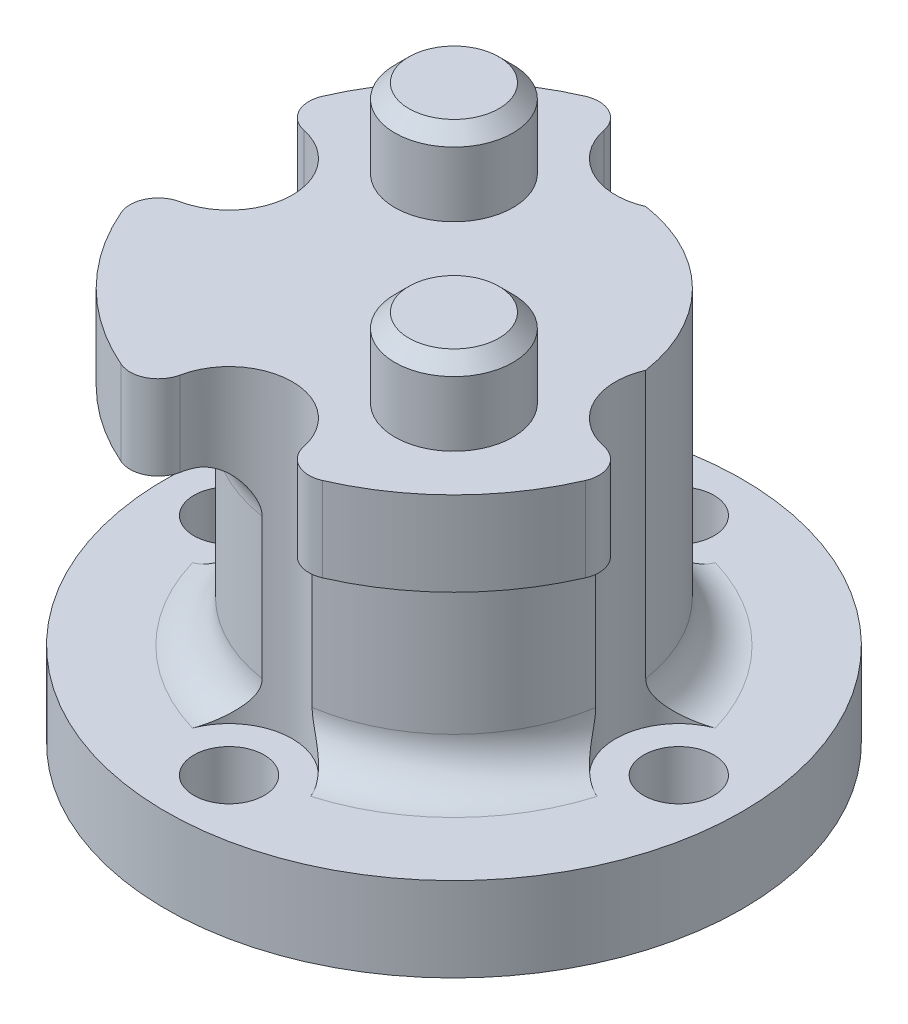
SolidWorks part; units mm, degrees
ref_plane "前视基准面" through (0, 0, 0) normal (0, 0, 1) x (1, 0, 0)
ref_plane "上视基准面" through (0, 0, 0) normal (0, 1, 0) x (1, 0, 0)
ref_plane "右视基准面" through (0, 0, 0) normal (1, 0, 0) x (0, 0, -1)
sketch "Sketch2" plane through (0, 0, 0) normal (0, 0, 1) x (1, 0, 0)
  line L0 (0, 0) -> (10.25, 0)
  line L1 (10.25, 0) -> (10.25, 3)
  line L2 (10.25, 3) -> (6, 3)
  line L3 (6, 3) -> (6, 11)
  line L4 (6, 11) -> (9, 11)
  line L5 (9, 11) -> (9, 14)
  line L6 (9, 14) -> (0, 14)
  line L7 (0, 14) -> (0, 0)
  line L8 (4.1, 0) -> (4.1, 2)
  line L9 (4.1, 2) -> (0, 2)
  dimension "D1" = 14
  dimension "D2" = 10.25
  dimension "D3" = 9
  dimension "D4" = 4.1
  dimension "D5" = 2
  dimension "D6" = 3
  dimension "D7" = 6
  dimension "D8" = 3
revolve "Revolve2" add sketch "Sketch2" angle 360 about L7
sketch "Sketch3" plane through (0, 0, 0) normal (0, -1, 0) x (1, 0, 0)
  line L0 (0, 0) -> (0, 8)
  circle A0 centre (0, 8) radius 1.25
  circle A1 centre (8, 0) radius 1.25
  circle A2 centre (0, -8) radius 1.25
  circle A3 centre (-8, 0) radius 1.25
  point P13 (0, 0)
  dimension "D2" = 2.5
  dimension "D1" = 8
  dimension "D3" = 4
extrude "Cut-Extrude1" cut sketch "Sketch3" against normal through all
sketch "Sketch4" plane through (0, 14, 0) normal (0, 1, 0) x (1, 0, 0)
  line L0 (0, 0) -> (0, 8)
  line L1 (0, 0) -> (-3.5355, 3.5355)
  circle A0 centre (-3.5355, 3.5355) radius 2.1
  circle A1 centre (3.5355, -3.5355) radius 2.1
  point P10 (0, 0)
  dimension "D3" = 4.2
  dimension "D1" = 45
  dimension "D2" = 5
  dimension "D4" = 2
extrude "Boss-Extrude1" add sketch "Sketch4" along normal blind 2.8
sketch "Sketch5" plane through (0, 3, 0) normal (0, 1, 0) x (1, 0, 0)
  circle A0 centre (0, 8) radius 1.25 construction
  circle A1 centre (8, 0) radius 1.25 construction
  circle A2 centre (0, -8) radius 1.25 construction
  circle A3 centre (-8, 0) radius 1.25 construction
  circle A4 centre (0, 8) radius 1.25
  circle A5 centre (8, 0) radius 1.25
  circle A6 centre (0, -8) radius 1.25
  circle A7 centre (-8, 0) radius 1.25
  circle A8 centre (0, -8) radius 2.25
  circle A9 centre (-8, 0) radius 2.25
  circle A10 centre (0, 8) radius 2.25
  circle A11 centre (8, 0) radius 2.25
  dimension "D1" = 1
extrude "Cut-Extrude2" cut sketch "Sketch5" along normal through all
fillet "Fillet1" radius 1.5 8 edges at (4.2426, 11, 4.2426) (-4.2426, 11, 4.2426) (-4.2426, 11, -4.2426) (4.2426, 11, -4.2426) (-4.2426, 3, -4.2426) (4.2426, 3, -4.2426) (4.2426, 3, 4.2426) (-4.2426, 3, 4.2426)
chamfer "Chamfer1" distance 0.5 angle 45 2 edges at (3.5355, 16.8, 5.6355) (-3.5355, 16.8, -1.4355)
fillet "Fillet2" radius 1 8 edges at (-8.7461, 12.5, 2.1227) (-8.7461, 12.5, -2.1227) (-2.1227, 12.5, -8.7461) (2.1227, 12.5, -8.7461) (8.7461, 12.5, -2.1227) (8.7461, 12.5, 2.1227) (2.1227, 12.5, 8.7461) (-2.1227, 12.5, 8.7461)
sketch "Sketch6" plane through (0, 14, 0) normal (0, 1, 0) x (1, 0, 0)
  line L0 (0.8902, 5.9336) -> (0.8902, 14.456)
  line L1 (0.8902, 14.456) -> (13.4991, 10.674)
  line L2 (13.4991, 10.674) -> (14.2473, 0.8902)
  line L3 (14.2473, 0.8902) -> (5.9336, 0.8902)
  arc A0 (0.8902, 5.9336) -> (5.9336, 0.8902) centre (0, 0) cw
  arc A1 (-2.1027, 7.1992) -> (2.1027, 7.1992) centre (0, 8) ccw construction
  arc A2 (7.543, 2.2031) -> (7.543, -2.2031) centre (8, 0) ccw construction
  dimension "D1" = 6
extrude "Cut-Extrude3" cut sketch "Sketch6" against normal blind 6
